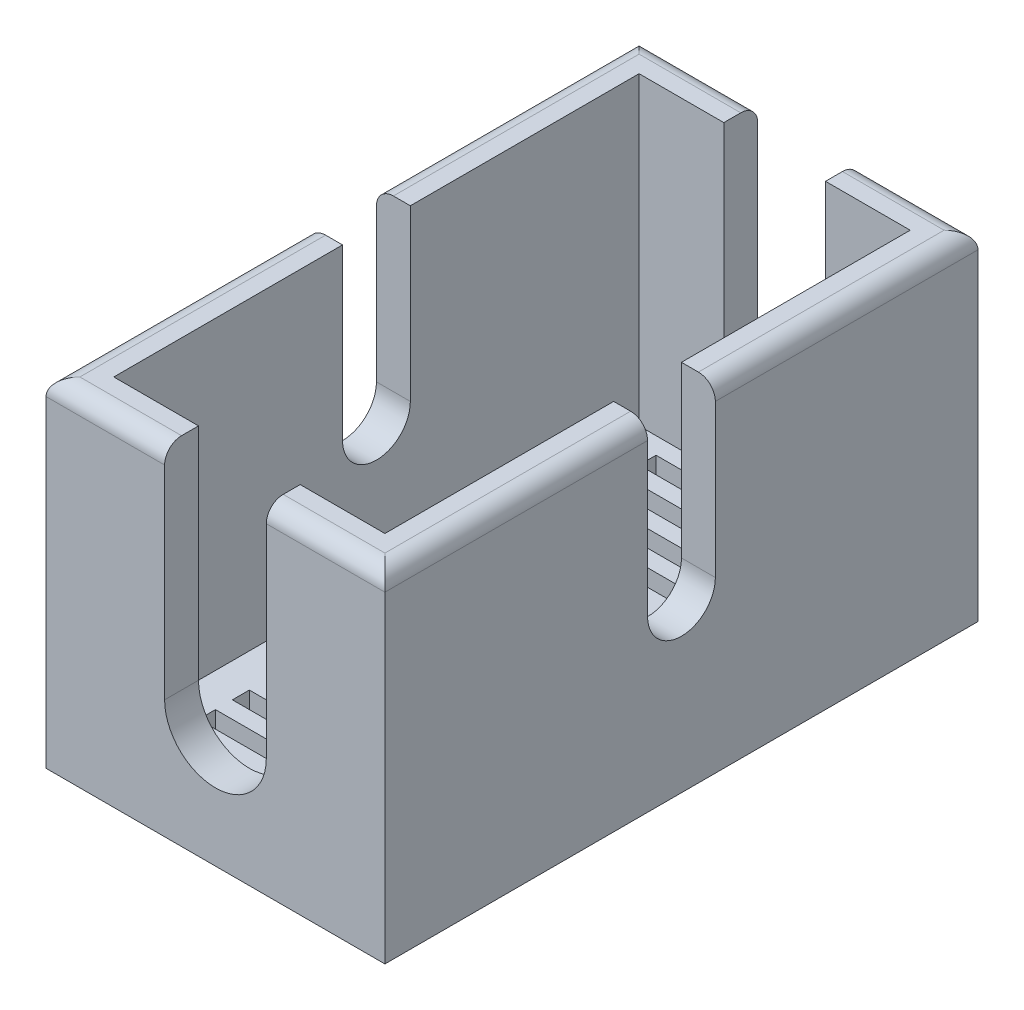
SolidWorks part; units mm, degrees
ref_plane "Ebene vorne" through (0, 0, 0) normal (0, 0, 1) x (1, 0, 0)
ref_plane "Ebene oben" through (0, 0, 0) normal (0, 1, 0) x (1, 0, 0)
ref_plane "Ebene rechts" through (0, 0, 0) normal (1, 0, 0) x (0, 0, -1)
sketch "Skizze1" plane through (0, 0, 0) normal (0, 0, 1) x (1, 0, 0)
  line L1 (0, 0) -> (20, 0)
  line L2 (0, 0) -> (0, 20)
  line L3 (0, 20) -> (20, 20)
  line L4 (20, 0) -> (20, 20)
  dimension "D1" = 20
  dimension "D2" = 20
extrude "Aufsatz-Linear austragen1" add sketch "Skizze1" along normal blind 35
shell "Wandung1" thickness 2
sketch "Skizze3" plane through (0, 0, 35) normal (0, 0, 1) x (1, 0, 0)
  line L0 (10, 20) -> (10, 7) construction
  line L1 (20, 20) -> (0, 20) construction
  line L2 (13, 20) -> (13, 7)
  line L3 (7, 20) -> (7, 7)
  arc A0 (13, 20) -> (7, 20) centre (10, 20) ccw
  arc A1 (7, 7) -> (13, 7) centre (10, 7) ccw
  point P4 (10, 13.5)
  dimension "D2" = 13
  dimension "D1" = 3
extrude "Schnitt-Linear austragen2" cut sketch "Skizze3" against normal up to surface (33 mm away)
ref_plane "Ebene1" through (0, 0, 17.5) normal (0, 0, 1) x (1, 0, 0)
mirror "Spiegeln1" about plane through (0, 0, 17.5) normal (0, 0, 1) of "Schnitt-Linear austragen2"
fillet "Verrundung1" radius 1 6 edges at (16.5, 20, 35) (3.5, 20, 35) (16.5, 20, 0) (3.5, 20, 0) (0, 20, 17.5) (20, 20, 17.5)
sketch "Skizze4" plane through (0, 2, 0) normal (0, 1, 0) x (1, 0, 0)
  line L1 (16, -18) -> (4, -18)
  line L2 (16, -18) -> (16, -17)
  line L3 (16, -17) -> (4, -17)
  line L4 (4, -18) -> (4, -17)
  line L6 (18, -33) -> (18, -2) construction
  line L7 (2, -33) -> (18, -33) construction
  point P6 (16, -17.5)
  dimension "D1" = 1
  dimension "D2" = 12
  dimension "D3" = 2
  dimension "D4" = 15.5
extrude "Schnitt-Linear austragen3" cut sketch "Skizze4" against normal up to surface (2 mm away) up to face at (10, 0, 17.5)
pattern_linear "Lineares Muster1" count 8 spacing 2 along (0, 0, 1) count 8 spacing 2 along (0, 0, -1) of "Schnitt-Linear austragen3"
sketch "Skizze5" plane through (0, 0, 0) normal (0, -1, 0) x (1, 0, 0)
  line L0 (10.45, 17.5) -> (-10.45, 17.5) construction
  line L1 (16, 10) -> (4, 10)
  line L2 (16, 10) -> (16, 25)
  line L3 (16, 25) -> (4, 25)
  line L4 (4, 10) -> (4, 25)
  line L5 (16, 10) -> (4, 25) construction
  line L6 (16, 25) -> (4, 10) construction
  point P0 (10, 17.5)
  dimension "D1" = 15
extrude "Aufsatz-Linear austragen2" add sketch "Skizze5" against normal up to surface (2 mm away) up to face at (10, 2, 3.5)
sketch "Skizze7" plane through (18, 0, 0) normal (-1, 0, 0) x (0, 0, 1)
  line L0 (17.5, 30) -> (17.5, 10) construction
  line L1 (33, 20) -> (2, 20) construction
  line L2 (17.5, -10.45) -> (17.5, 10.45) construction
  line L3 (19.5, 30) -> (19.5, 10)
  line L4 (15.5, 30) -> (15.5, 10)
  arc A0 (19.5, 30) -> (15.5, 30) centre (17.5, 30) ccw
  arc A1 (15.5, 10) -> (19.5, 10) centre (17.5, 10) ccw
  point P6 (17.5, 20)
  point P11 (17.5, 12)
  dimension "D2" = 2
  dimension "D1" = 8
extrude "Schnitt-Linear austragen4" cut sketch "Skizze7" against normal up to surface and the other way up to surface up to face at (20, 9.5, 17.5) other way up to face at (0, 9.5, 17.5)
